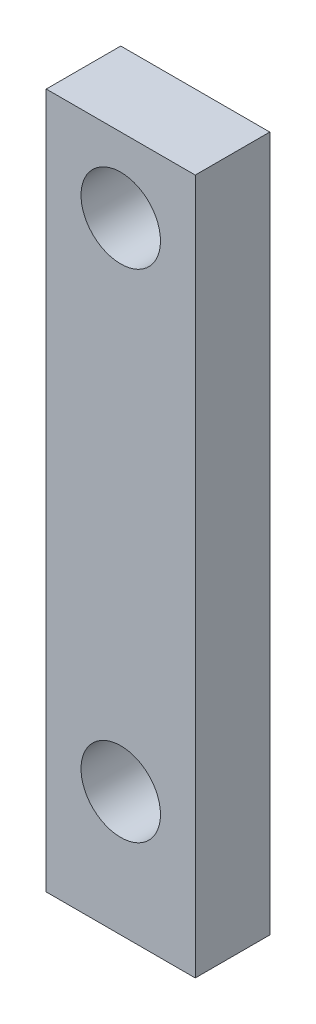
SolidWorks part; units mm, degrees
ref_plane "Přední rovina" through (0, 0, 0) normal (0, 0, 1) x (1, 0, 0)
ref_plane "Horní rovina" through (0, 0, 0) normal (0, 1, 0) x (1, 0, 0)
ref_plane "Pravá rovina" through (0, 0, 0) normal (1, 0, 0) x (0, 0, -1)
sketch "Skica1" plane through (0, 0, 0) normal (0, 0, 1) x (1, 0, 0)
  line L1 (-4.5243, 54.3) -> (-10.5243, 54.3)
  line L2 (-4.5243, 54.3) -> (-4.5243, 82.3)
  line L3 (-4.5243, 82.3) -> (-10.5243, 82.3)
  line L4 (-10.5243, 54.3) -> (-10.5243, 82.3)
  circle A0 centre (-7.5243, 59.3) radius 1.6
  circle A1 centre (-7.5243, 79.3) radius 1.6
extrude "Přidat vysunutím1" add sketch "Skica1" along normal blind 3
